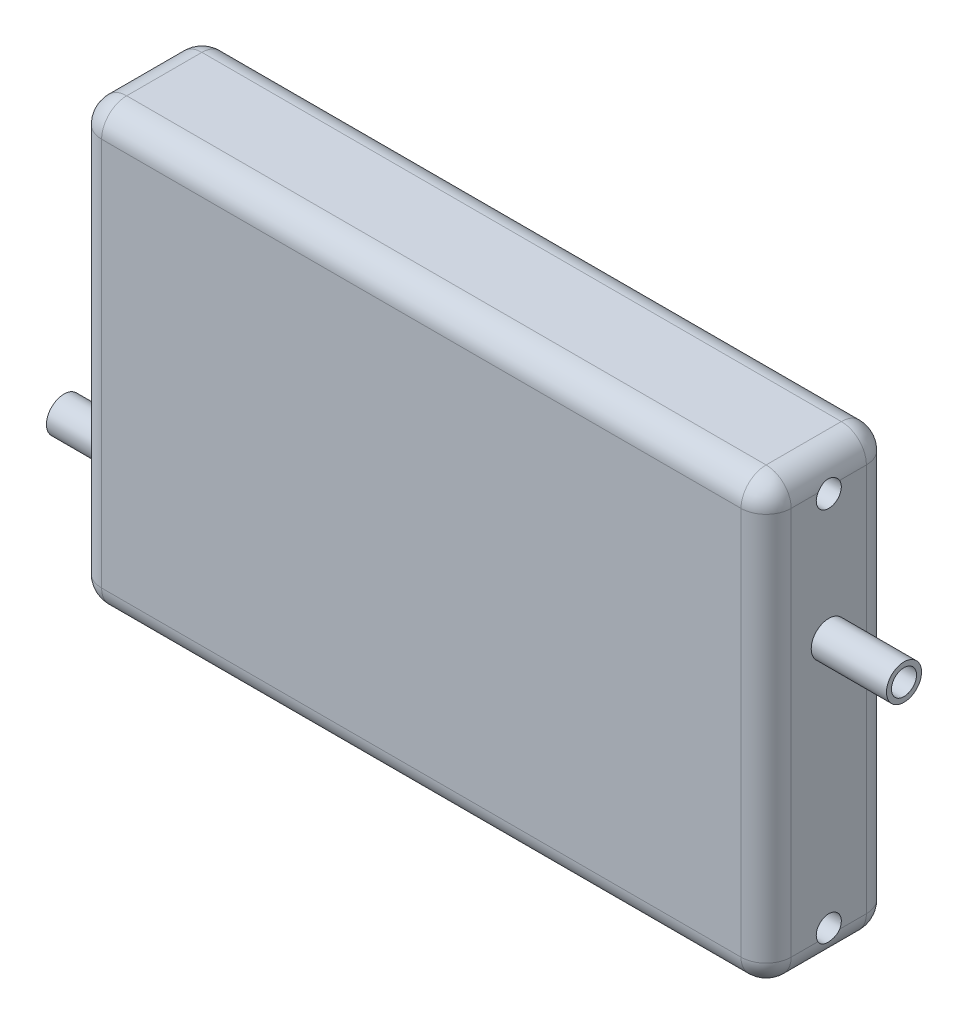
SolidWorks part; units mm, degrees
material "ABS PC"
ref_plane "Front Plane" through (0, 0, 0) normal (0, 0, 1) x (1, 0, 0)
ref_plane "Top Plane" through (0, 0, 0) normal (0, 1, 0) x (1, 0, 0)
ref_plane "Right Plane" through (0, 0, 0) normal (1, 0, 0) x (0, 0, -1)
sketch "Sketch1" plane through (0, 0, 0) normal (0, 0, 1) x (1, 0, 0)
  line L1 (137.5, -87.5) -> (-137.5, -87.5)
  line L2 (137.5, -87.5) -> (137.5, 87.5)
  line L3 (137.5, 87.5) -> (-137.5, 87.5)
  line L4 (-137.5, -87.5) -> (-137.5, 87.5)
  line L5 (137.5, -87.5) -> (-137.5, 87.5) construction
  line L6 (137.5, 87.5) -> (-137.5, -87.5) construction
  point P0 (0, 0)
  dimension "D1" = 275
  dimension "D2" = 175
extrude "Boss-Extrude1" add sketch "Sketch1" along normal mid plane 50
fillet "Fillet1" radius 10 12 edges at (0, -87.5, 25) (0, -87.5, -25) (0, 87.5, 25) (0, 87.5, -25) (-137.5, 87.5, 0) (-137.5, 0, 25) (-137.5, -87.5, 0) (-137.5, 0, -25) (137.5, -87.5, 0) (137.5, 0, 25) (137.5, 87.5, 0) (137.5, 0, -25)
sketch "Sketch2" plane through (137.5, 0, 0) normal (1, 0, 0) x (0, 0, -1)
  line L0 (0, 87.5) -> (0, -87.5) construction
  line L1 (-15, 87.5) -> (15, 87.5) construction
  line L2 (15, -87.5) -> (-15, -87.5) construction
  circle A0 centre (0, 75) radius 5
  circle A1 centre (0, 25) radius 5
  circle A2 centre (0, -75) radius 5
  point P13 (0, 0)
  dimension "D1" = 10
  dimension "D2" = 10
  dimension "D5" = 75
  dimension "D6" = 10
  dimension "D3" = 25
  dimension "D4" = 75
extrude "Cut-Extrude1" cut sketch "Sketch2" against normal blind 180
sketch "Sketch3" plane through (0, 0, 0) normal (1, 0, 0) x (0, 0, -1)
  line L0 (0, 70) -> (0, -41.6368) construction
  line L1 (25, 77.5) -> (25, -77.5) construction
  line L2 (-15, 82.5) -> (15, 82.5)
  line L3 (-20, 77.5) -> (-20, -77.5678)
  line L4 (-15, -82.5678) -> (15, -82.5678)
  line L5 (20, 77.5) -> (20, -77.5678)
  line L6 (-20, 82.5) -> (20, -82.5678) construction
  line L7 (-20, -82.5678) -> (20, 82.5) construction
  line L8 (-34.9444, -0.0339) -> (44.2274, -0.0339) construction
  line L9 (-15, 87.5) -> (15, 87.5) construction
  circle A0 centre (0, 75) radius 5 construction
  arc A1 (-20, 77.5) -> (-15, 82.5) centre (-15, 77.5) cw
  arc A2 (15, 82.5) -> (20, 77.5) centre (15, 77.5) cw
  arc A3 (15, -82.5678) -> (20, -77.5678) centre (15, -77.5678) ccw
  arc A4 (-20, -77.5678) -> (-15, -82.5678) centre (-15, -77.5678) ccw
  point P5 (0, -0.0339)
  dimension "D3" = 5
  dimension "D1" = 5
  dimension "D2" = 5
extrude "Cut-Extrude2" cut sketch "Sketch3" against normal mid plane 250
sketch "Sketch5" plane through (-137.5, 0, 0) normal (-1, 0, 0) x (0, 0, 1)
  line L0 (0, 48.5762) -> (0, -27.7578) construction
  circle A0 centre (0, -50) radius 5
  dimension "D1" = 50
  dimension "D2" = 10
extrude "Cut-Extrude3" cut sketch "Sketch5" against normal blind 190
sketch "Sketch6" plane through (137.5, 0, 0) normal (1, 0, 0) x (0, 0, -1)
  circle A0 centre (0, 25) radius 7
  circle A1 centre (0, 25) radius 5
  dimension "D1" = 14
extrude "Boss-Extrude2" add sketch "Sketch6" along normal blind 30
sketch "Sketch7" plane through (-137.5, 0, 0) normal (-1, 0, 0) x (0, 0, 1)
  circle A0 centre (0, -50) radius 7
  circle A1 centre (0, -50) radius 5
  dimension "D1" = 14
extrude "Boss-Extrude3" add sketch "Sketch7" along normal blind 30
